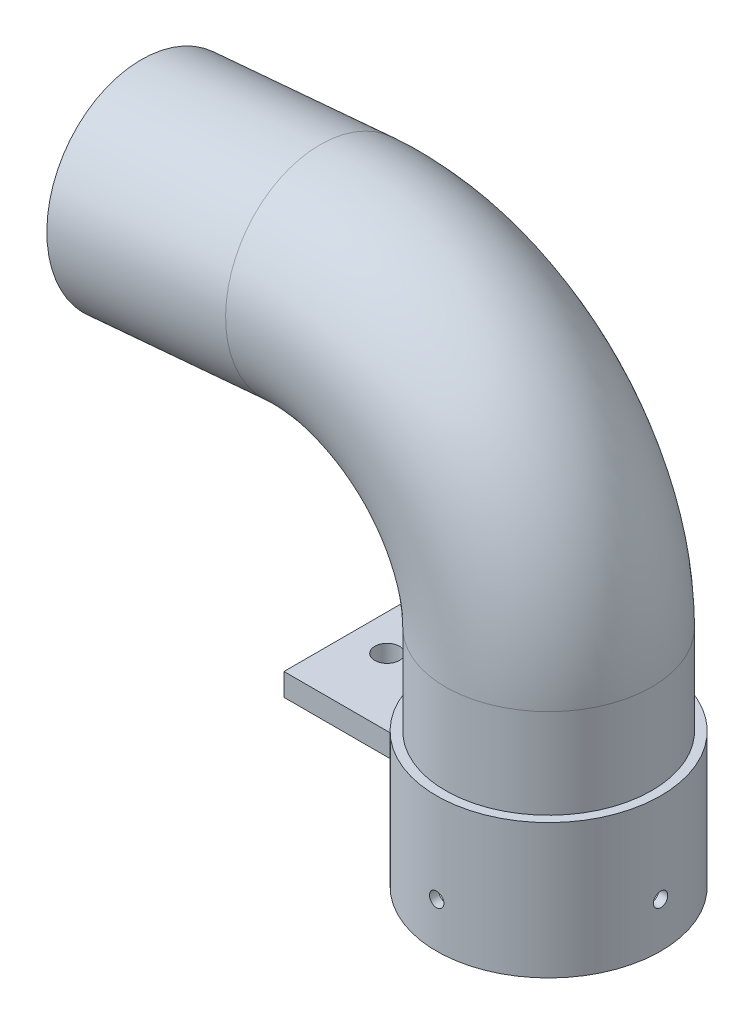
SolidWorks part; units mm, degrees
ref_plane "前视基准面" through (0, 0, 0) normal (0, 0, 1) x (1, 0, 0)
ref_plane "上视基准面" through (0, 0, 0) normal (0, 1, 0) x (1, 0, 0)
ref_plane "右视基准面" through (0, 0, 0) normal (1, 0, 0) x (0, 0, -1)
sketch "草图1" plane through (0, 0, 0) normal (0, 1, 0) x (1, 0, 0)
  circle A0 centre (0, 0) radius 21
  circle A1 centre (0, 0) radius 23
  dimension "D1" = 42
  dimension "D2" = 46
sketch "草图2" plane through (0, 0, 0) normal (0, 0, 1) x (1, 0, 0)
  line L0 (0, 0) -> (0, 30)
  line L3 (-48.922, 74.8288) -> (-88.7698, 71.3425)
  arc A0 (-48.922, 74.8288) -> (0, 30) centre (-45, 30) cw
  dimension "D2" = 85
  dimension "D3" = 45
  dimension "D5" = 30
  dimension "D1" = 40
sweep "扫描1" add profiles "草图1" path "草图2"
sketch "草图3" plane through (0, 0, 58.7657) normal (0, -1, 0) x (1, 0, 0)
  circle A0 centre (0, -58.7657) radius 23
  circle A1 centre (0, -58.7657) radius 25
  circle A3 centre (0, -58.7657) radius 21 construction
  dimension "D1" = 46
  dimension "D2" = 50
extrude "凸台-拉伸1" add sketch "草图3" along normal blind 20 and the other way blind 10 separate body
ref_plane "基准面1" through (0, 2, 0) normal (0, -1, 0) x (-1, 0, 0)
sketch "草图5" plane through (0, 2, 0) normal (0, -1, 0) x (-1, 0, 0)
  line L0 (20, 15) -> (44, 15)
  line L1 (44, 15) -> (44, -15)
  line L2 (44, -15) -> (20, -15)
  line L3 (0, 0) -> (16.9639, 0) construction
  arc A0 (20, -15) -> (20, 15) centre (0, 0) ccw
  circle A1 centre (0, 0) radius 25 construction
  circle A2 centre (36, 0) radius 2.75
  dimension "D3" = 5.5
  dimension "D1" = 30
  dimension "D2" = 8
  dimension "D4" = 36
extrude "凸台-拉伸3" add sketch "草图5" against normal blind 5
sketch "草图6" plane through (0, 0, 0) normal (1, 0, 0) x (0, 0, -1)
  line L0 (-25, -20) -> (25, -20) construction
  line L1 (0, -10) -> (0, -20) construction
  circle A0 centre (0, -10) radius 1.6
  dimension "D1" = 3.2
  dimension "D2" = 10
extrude "切除-拉伸1" cut sketch "草图6" against normal through all and the other way through all
sketch "草图7" plane through (0, 0, 0) normal (0, 0, 1) x (1, 0, 0)
  line L0 (-25, -20) -> (25, -20) construction
  line L1 (0, -10) -> (0, -20) construction
  circle A0 centre (0, -10) radius 1.6
  dimension "D1" = 3.2
  dimension "D2" = 10
extrude "切除-拉伸2" cut sketch "草图7" against normal through all and the other way through all
ref_plane "基准面2" through (-90, 0, 0) normal (1, 0, 0) x (0, 0, -1)
sketch "草图8" plane through (-90, 0, 0) normal (1, 0, 0) x (0, 0, -1)
  line L1 (-41.0022, 111.3769) -> (51.8758, 111.3769)
  line L2 (-41.0022, 111.3769) -> (-41.0022, 19.8581)
  line L3 (-41.0022, 19.8581) -> (51.8758, 19.8581)
  line L4 (51.8758, 111.3769) -> (51.8758, 19.8581)
